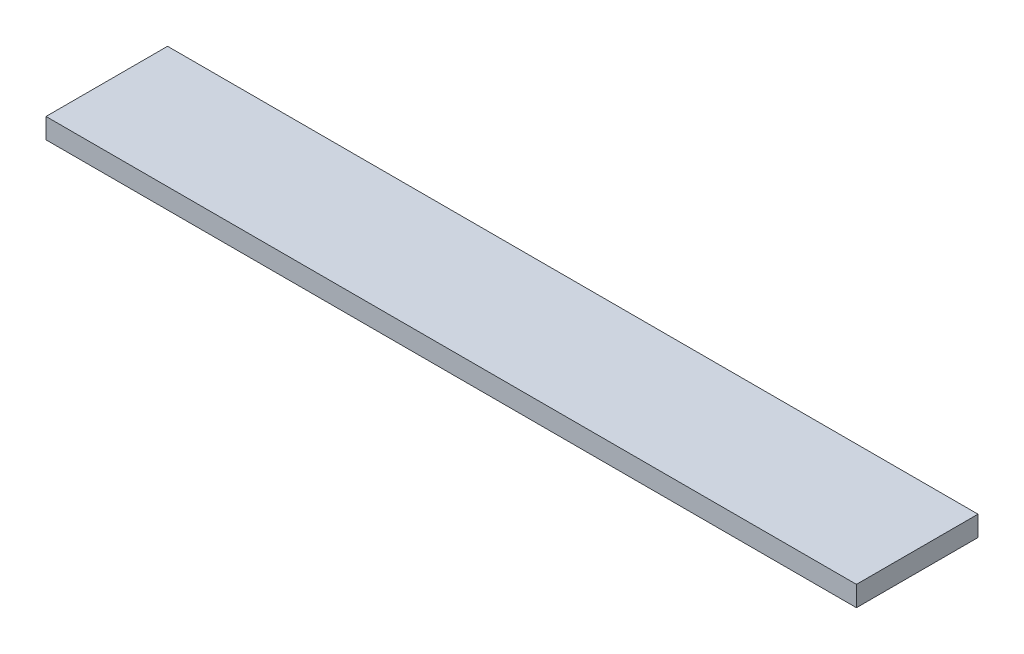
SolidWorks part; units mm, degrees
ref_plane "Front Plane" through (0, 0, 0) normal (0, 0, 1) x (1, 0, 0)
ref_plane "Top Plane" through (0, 0, 0) normal (0, 1, 0) x (1, 0, 0)
ref_plane "Right Plane" through (0, 0, 0) normal (1, 0, 0) x (0, 0, -1)
sketch "Sketch1" plane through (0, 0, 0) normal (0, 0, 1) x (1, 0, 0)
  line L1 (-27.3111, 16.1056) -> (12.6889, 16.1056)
  line L2 (-27.3111, 16.1056) -> (-27.3111, 10.1056)
  line L3 (-27.3111, 10.1056) -> (12.6889, 10.1056)
  line L4 (12.6889, 16.1056) -> (12.6889, 10.1056)
  line L5 (-7.3111, 10.1056) -> (-7.3111, 16.1056) construction
  line L6 (-27.3111, 13.1056) -> (12.6889, 13.1056) construction
  point P104 (-7.3111, 13.1056)
  dimension "D1" = 6
  dimension "D2" = 40
extrude "Boss-Extrude1" add sketch "Sketch1" along normal blind 1
move or copy body "Body-Move/Copy1" bodies to move or copy 102 copy no rotation origin (0, 13.1056, 0.25) rotation axis (1, 0, 0) rotation angle 90
